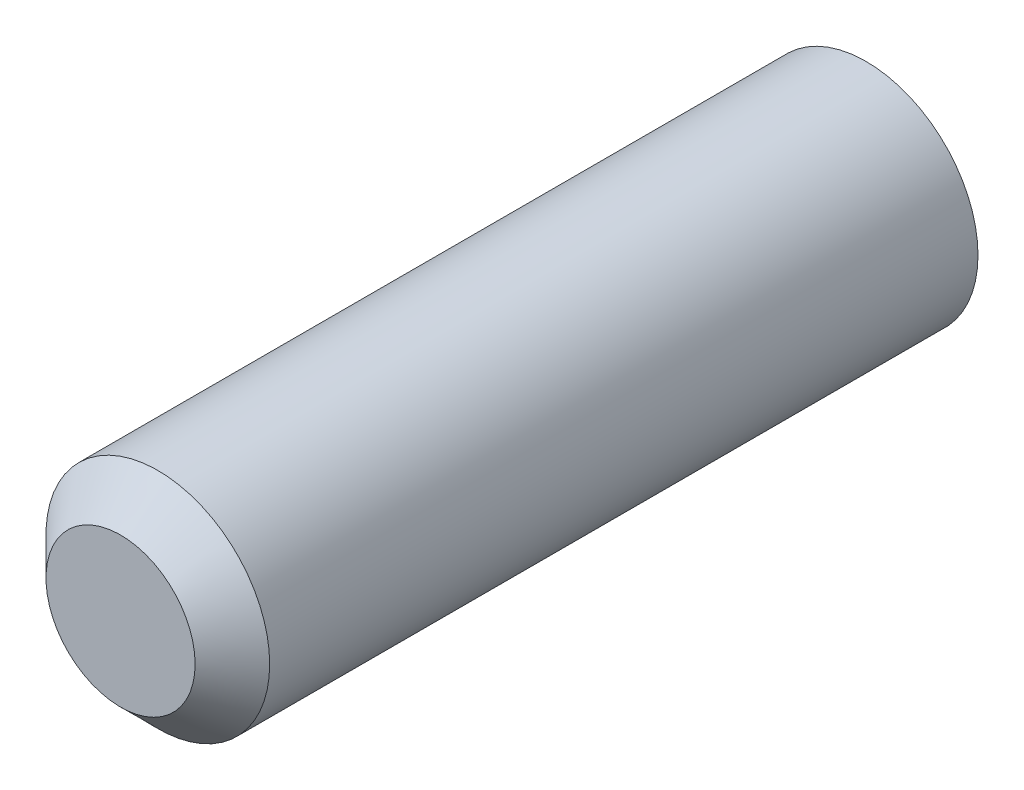
SolidWorks part; units mm, degrees
ref_plane "Plan de face" through (0, 0, 0) normal (0, 0, 1) x (1, 0, 0)
ref_plane "Plan de dessus" through (0, 0, 0) normal (0, 1, 0) x (1, 0, 0)
ref_plane "Plan de droite" through (0, 0, 0) normal (1, 0, 0) x (0, 0, -1)
sketch "Esquisse1" plane through (0, 0, 0) normal (0, 0, 1) x (1, 0, 0)
  circle A0 centre (0, 0) radius 1.5
  dimension "D1" = 3
extrude "Extrusion1" add sketch "Esquisse1" along normal blind 10
chamfer "Chanfrein1" distance 0.5 angle 45 1 edges at (1.5, 0, 10)
